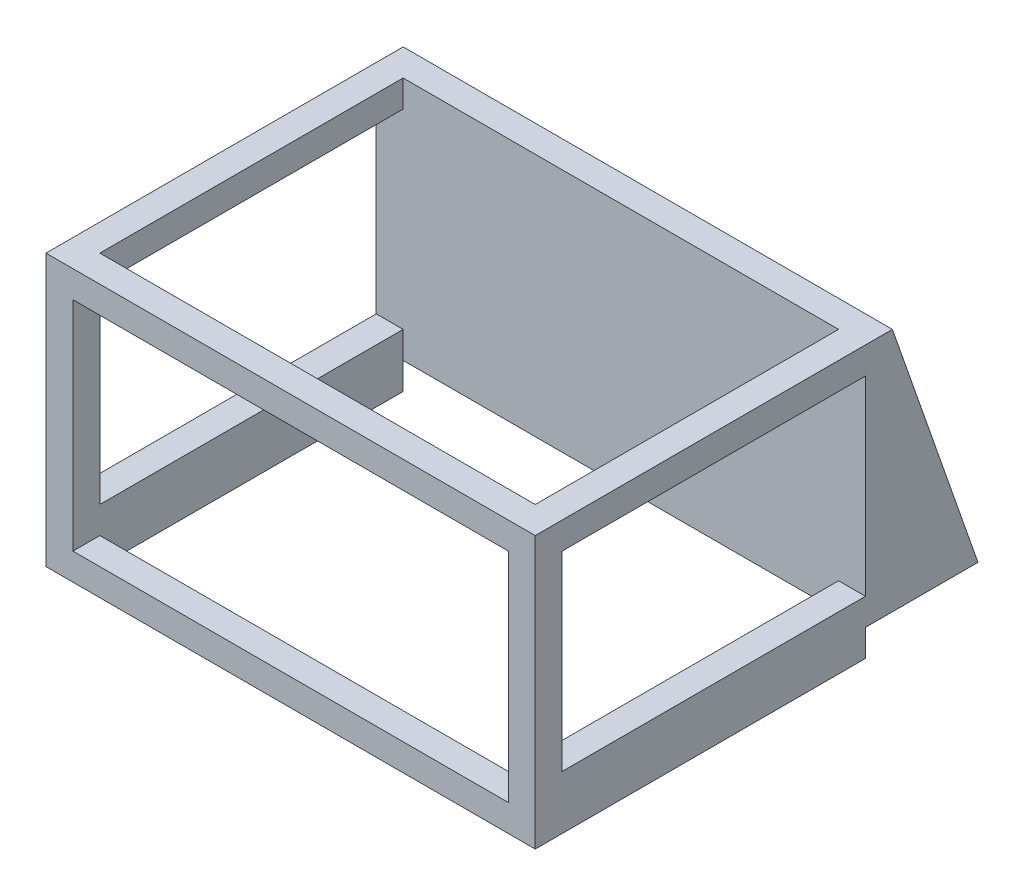
SolidWorks part; units mm, degrees
ref_plane "Plan de face" through (0, 0, 0) normal (0, 0, 1) x (1, 0, 0)
ref_plane "Plan de dessus" through (0, 0, 0) normal (0, 1, 0) x (1, 0, 0)
ref_plane "Plan de droite" through (0, 0, 0) normal (1, 0, 0) x (0, 0, -1)
sketch "Esquisse1" plane through (0, 0, 0) normal (0, 0, 1) x (1, 0, 0)
  line L1 (-180.0766, 91.5709) -> (219.9234, 91.5709)
  line L2 (-180.0766, 91.5709) -> (-180.0766, -130.4291)
  line L3 (-180.0766, -130.4291) -> (219.9234, -130.4291)
  line L4 (219.9234, 91.5709) -> (219.9234, -130.4291)
  dimension "D1" = 400
  dimension "D2" = 222
extrude "Boss.-Extru.1" add sketch "Esquisse1" along normal blind 292
sketch "Esquisse2" plane through (0, -130.4291, 0) normal (0, -1, 0) x (1, 0, 0)
  line L0 (-180.0766, 292) -> (219.9234, 292) construction
  line L1 (-158.0766, 270) -> (197.9234, 270)
  line L2 (-158.0766, 270) -> (-158.0766, 0)
  line L3 (-158.0766, 0) -> (197.9234, 0)
  line L4 (197.9234, 270) -> (197.9234, 0)
  line L6 (219.9234, 292) -> (219.9234, 0) construction
  line L7 (-180.0766, 292) -> (-180.0766, 0) construction
  line L8 (-180.0766, 0) -> (219.9234, 0) construction
  dimension "D1" = 22
  dimension "D2" = 0
  dimension "D3" = 22
  dimension "D4" = 22
extrude "Enlèv. mat.-Extru.1" cut sketch "Esquisse2" against normal through all
sketch "Esquisse8" plane through (219.9234, 0, 0) normal (1, 0, 0) x (0, 0, -1)
  line L0 (0, -130.4291) -> (0, 91.5709) construction
  line L1 (-270, 69.5709) -> (0, 69.5709)
  line L2 (-270, 69.5709) -> (-270, -86.4291)
  line L3 (-270, -86.4291) -> (0, -86.4291)
  line L4 (0, 69.5709) -> (0, -86.4291)
  line L5 (-292, 91.5709) -> (0, 91.5709) construction
  line L6 (-292, -130.4291) -> (0, -130.4291) construction
  line L7 (-292, -130.4291) -> (-292, 91.5709) construction
  dimension "D1" = 22
  dimension "D2" = 44
  dimension "D3" = 22
extrude "Enlèv. mat.-Extru.2" cut sketch "Esquisse8" against normal through all
sketch "Esquisse9" plane through (0, 0, 292) normal (0, 0, 1) x (1, 0, 0)
  line L0 (219.9234, 91.5709) -> (-180.0766, 91.5709) construction
  line L1 (-158.0766, 69.5709) -> (197.9234, 69.5709)
  line L2 (-158.0766, 69.5709) -> (-158.0766, -108.4291)
  line L3 (-158.0766, -108.4291) -> (197.9234, -108.4291)
  line L4 (197.9234, 69.5709) -> (197.9234, -108.4291)
  line L5 (219.9234, -130.4291) -> (219.9234, 91.5709) construction
  line L6 (-180.0766, -130.4291) -> (219.9234, -130.4291) construction
  line L7 (-180.0766, 91.5709) -> (-180.0766, -130.4291) construction
  dimension "D1" = 22
  dimension "D2" = 22
  dimension "D3" = 22
  dimension "D4" = 22
extrude "Enlèv. mat.-Extru.3" cut sketch "Esquisse9" against normal through all
sketch "Esquisse10" plane through (219.9234, 0, 0) normal (1, 0, 0) x (0, 0, -1)
  line L1 (0, -130.4291) -> (-22, -130.4291)
  line L2 (0, -130.4291) -> (0, -108.4291)
  line L3 (0, -108.4291) -> (-22, -108.4291)
  line L4 (-22, -130.4291) -> (-22, -108.4291)
  dimension "D1" = 22
  dimension "D2" = 22
extrude "Enlèv. mat.-Extru.4" cut sketch "Esquisse10" against normal blind 400
sketch "Esquisse11" plane through (219.9234, 0, 0) normal (1, 0, 0) x (0, 0, -1)
  line L1 (0, -108.4291) -> (-22, -108.4291)
  line L2 (0, -108.4291) -> (0, 91.5709)
  line L3 (-22, -108.4291) -> (-22, 91.5709)
  line L4 (0, 91.5709) -> (-22, 91.5709)
  dimension "D1" = 200
extrude "Boss.-Extru.2" add sketch "Esquisse11" against normal blind 400
sketch "Esquisse12" plane through (219.9234, 0, 0) normal (1, 0, 0) x (0, 0, -1)
  line L0 (70, -108.4291) -> (0, 91.5709)
  line L1 (0, -108.4291) -> (70, -108.4291)
  line L2 (0, -108.4291) -> (0, 91.5709)
  dimension "D1" = 200
  dimension "D2" = 70
extrude "Boss.-Extru.3" add sketch "Esquisse12" against normal blind 22
sketch "Esquisse13" plane through (-180.0766, 0, 0) normal (-1, 0, 0) x (0, 0, 1)
  line L1 (0, -108.4291) -> (-70, -108.4291)
  line L3 (0, 91.5709) -> (-70, -108.4291)
  line L6 (0, -108.4291) -> (0, 91.5709)
  dimension "D1" = 200
  dimension "D2" = 70
extrude "Boss.-Extru.4" add sketch "Esquisse13" against normal blind 22
